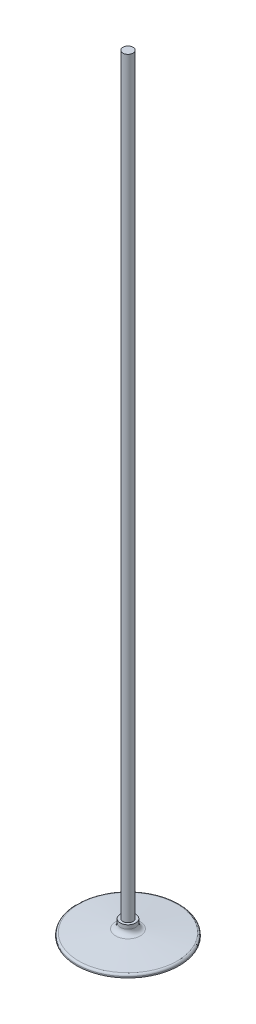
SolidWorks part; units mm, degrees
ref_plane "Front Plane" through (0, 0, 0) normal (0, 0, 1) x (1, 0, 0)
ref_plane "Top Plane" through (0, 0, 0) normal (0, 1, 0) x (1, 0, 0)
ref_plane "Right Plane" through (0, 0, 0) normal (1, 0, 0) x (0, 0, -1)
sketch "Sketch1" plane through (0, 0, 0) normal (0, 0, 1) x (1, 0, 0)
  line L0 (0, 0) -> (-100, 0)
  line L1 (-100, 0) -> (-100, 6)
  line L2 (-100, 6) -> (-15, 13.4365)
  line L3 (-10, 30) -> (-10, 1500)
  line L4 (-10, 1500) -> (0, 1500)
  line L5 (0, 1500) -> (0, 0)
  line L6 (0, 0) -> (0, -24.5544) construction
  line L7 (-15, 13.4365) -> (-15, 30)
  line L8 (-15, 30) -> (-10, 30)
  dimension "D1" = 200
  dimension "D2" = 20
  dimension "D3" = 5
  dimension "D4" = 6
  dimension "D5" = 1500
  dimension "D6" = 30
  dimension "D7" = 30
revolve "Revolve1" add sketch "Sketch1" angle 360 about L6
fillet "Fillet1" radius 4 1 edges at (0, 6, 100)
fillet "Fillet2" radius 10 1 edges at (0, 13.4365, 15)
